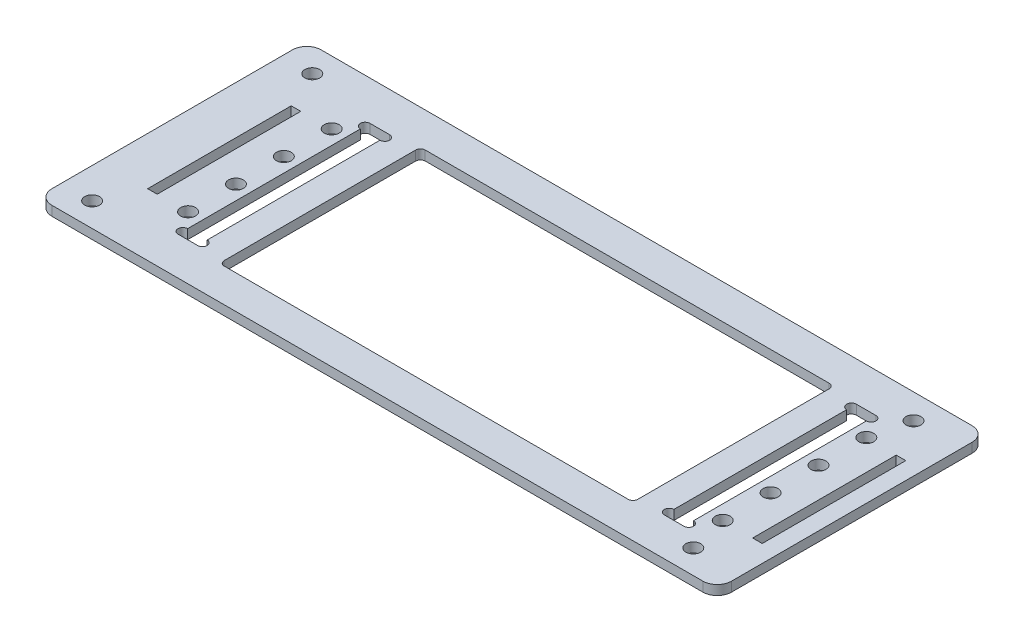
SolidWorks part; units mm, degrees
material "VMA 碳纤维"
ref_plane "前视基准面" through (0, 0, 0) normal (0, 0, 1) x (1, 0, 0)
ref_plane "上视基准面" through (0, 0, 0) normal (0, 1, 0) x (1, 0, 0)
ref_plane "右视基准面" through (0, 0, 0) normal (1, 0, 0) x (0, 0, -1)
other "Configuration Table"
sketch "草图1" plane through (0, 0, 0) normal (0, 1, 0) x (1, 0, 0)
  line L0 (-67.2, 28.25) -> (-74.2, 28.25)
  line L1 (-43.2, -21) -> (43.2, -21)
  line L2 (-43.2, -21) -> (-43.2, 21)
  line L3 (-43.2, 21) -> (43.2, 21)
  line L4 (43.2, -21) -> (43.2, 21)
  line L5 (-43.2, -21) -> (43.2, 21) construction
  line L6 (-43.2, 21) -> (43.2, -21) construction
  line L7 (-67.2, 28.25) -> (67.8, 28.25)
  line L8 (-67.2, 28.25) -> (-67.2, -28) construction
  line L9 (-67.2, -28) -> (67.8, -28)
  line L10 (67.8, 28.25) -> (67.8, -28)
  line L11 (-67.2, 28.25) -> (67.8, -28) construction
  line L12 (-67.2, -28) -> (67.8, 28.25) construction
  line L13 (-74.2, 28.25) -> (-74.2, -28)
  line L14 (-74.2, -28) -> (-67.2, -28)
  point P0 (0, 0)
  point P6 (0, 0)
  dimension "D1" = 86.4
  dimension "D2" = 42
  dimension "D3" = 7
  dimension "D4" = 24.6
  dimension "D5" = 24
  dimension "D6" = 7
extrude "凸台-拉伸1" add sketch "草图1" along normal blind 2
sketch "草图2" plane through (0, 2, 0) normal (0, 1, 0) x (1, 0, 0)
  line L0 (-50.75, 0) -> (0, 0) construction
  line L1 (0, 0) -> (50.85, 0) construction
  line L2 (-43.2, 21) -> (-43.2, -21) construction
  line L3 (-52.8, -20.05) -> (-48.7, -20.05)
  line L4 (-52.8, -20.05) -> (-52.8, 20.05)
  line L5 (-52.8, 20.05) -> (-48.7, 20.05)
  line L6 (-48.7, -20.05) -> (-48.7, 20.05)
  line L7 (-52.8, -20.05) -> (-48.7, 20.05) construction
  line L8 (-52.8, 20.05) -> (-48.7, -20.05) construction
  line L9 (43.2, -21) -> (43.2, 21) construction
  line L10 (48.8, -20.05) -> (52.9, -20.05)
  line L11 (48.8, -20.05) -> (48.8, 20.05)
  line L12 (48.8, 20.05) -> (52.9, 20.05)
  line L13 (52.9, -20.05) -> (52.9, 20.05)
  line L14 (48.8, -20.05) -> (52.9, 20.05) construction
  line L15 (48.8, 20.05) -> (52.9, -20.05) construction
  dimension "D1" = 5.5
  dimension "D2" = 5.6
  dimension "D3" = 40.1
  dimension "D4" = 4.1
extrude "切除-拉伸1" cut sketch "草图2" against normal blind 2
sketch "草图4" plane through (0, 2, 0) normal (0, 1, 0) x (1, 0, 0)
  line L0 (-52.8, 20.05) -> (-52.8, -20.05) construction
  line L1 (-48.7, -20.05) -> (-48.7, 20.05) construction
  line L2 (48.8, 20.05) -> (48.8, -20.05) construction
  line L3 (52.9, -20.05) -> (52.9, 20.05) construction
  circle A0 centre (-52.8, 19.05) radius 1
  circle A1 centre (-48.7, 19.05) radius 1
  circle A2 centre (-52.8, -19.05) radius 1
  circle A3 centre (-48.7, -19.05) radius 1
  circle A4 centre (48.8, -19.05) radius 1
  circle A5 centre (52.9, -19.05) radius 1
  circle A6 centre (52.9, 19.05) radius 1
  circle A7 centre (48.8, 19.05) radius 1
  dimension "D1" = 2
extrude "切除-拉伸2" cut sketch "草图4" against normal blind 2
sketch "草图5" plane through (0, 2, 0) normal (0, 1, 0) x (1, 0, 0)
  line L0 (0, 0) -> (55.9, 0) construction
  line L1 (55.9, 0) -> (55.9, 15.05) construction
  line L2 (52.9, 20.05) -> (48.8, 20.05) construction
  line L3 (55.9, 15.05) -> (55.9, 5.05) construction
  line L4 (52.9, -18.05) -> (52.9, 18.05) construction
  line L5 (0, 0) -> (-55.8, 0) construction
  line L6 (-55.8, 0) -> (-55.8, 15.05) construction
  line L7 (-48.7, 20.05) -> (-52.8, 20.05) construction
  line L8 (-52.8, 18.05) -> (-52.8, -18.05) construction
  line L9 (-55.8, 15.05) -> (-55.8, 5.05) construction
  circle A0 centre (55.9, 15.05) radius 1.55
  circle A1 centre (55.9, 5.05) radius 1.55
  circle A2 centre (55.9, -4.95) radius 1.55
  circle A3 centre (55.9, -14.95) radius 1.55
  circle A4 centre (-55.8, 15.05) radius 1.55
  circle A5 centre (-55.8, 5.05) radius 1.55
  circle A6 centre (-55.8, -4.95) radius 1.55
  circle A7 centre (-55.8, -14.95) radius 1.55
  dimension "D4" = 3.1
  dimension "D6" = 5
  dimension "D8" = 3.1
  dimension "D1" = 5
  dimension "D3" = 10
  dimension "D5" = 3
  dimension "D7" = 3
  dimension "D10" = 10
  dimension "D2" = 4
  dimension "D9" = 4
extrude "切除-拉伸3" cut sketch "草图5" against normal blind 2
sketch "草图6" plane through (0, 2, 0) normal (0, 1, 0) x (1, 0, 0)
  line L0 (0, 0) -> (0, -51.7988) construction
  line L1 (-74.2, -28) -> (67.8, -28) construction
  line L2 (67.8, -28) -> (67.8, 28.25) construction
  line L3 (0, 0) -> (28.8222, 0) construction
  circle A0 centre (57.8, -23) radius 1.55
  circle A1 centre (57.8, 23) radius 1.55
  circle A2 centre (-57.8, -23) radius 1.55 construction
  circle A3 centre (-57.8, 23) radius 1.55 construction
  circle A4 centre (-67.8, -23) radius 1.55
  circle A5 centre (-67.8, 23) radius 1.55
  dimension "D2" = 10
  dimension "D3" = 3.1
  dimension "D1" = 5
  dimension "D5" = 10
  dimension "D4" = 2
extrude "切除-拉伸4" cut sketch "草图6" against normal blind 2
sketch "草图7" plane through (0, 2, 0) normal (0, 1, 0) x (1, 0, 0)
  line L1 (-64.2, 15) -> (-62.2, 15)
  line L2 (-64.2, 15) -> (-64.2, -15)
  line L3 (-64.2, -15) -> (-62.2, -15)
  line L4 (-62.2, 15) -> (-62.2, -15)
  line L5 (-64.2, 0) -> (0, 0) construction
  line L6 (0, 0) -> (0, -11.8021) construction
  line L7 (64.2, -15) -> (62.2, -15)
  line L8 (62.2, 15) -> (62.2, -15)
  line L9 (64.2, 15) -> (62.2, 15)
  line L10 (64.2, 15) -> (64.2, -15)
  line L11 (-74.2, 28.25) -> (-74.2, -28) construction
  dimension "D1" = 10
  dimension "D2" = 30
  dimension "D3" = 2
extrude "切除-拉伸5" cut sketch "草图7" against normal blind 2
fillet "圆角1" radius 1 4 edges at (-43.2, 1, -21) (43.2, 1, 21) (43.2, 1, -21) (-43.2, 1, 21)
fillet "圆角2" radius 3 4 edges at (67.8, 1, 28) (67.8, 1, -28.25) (-74.2, 1, 28) (-74.2, 1, -28.25)
